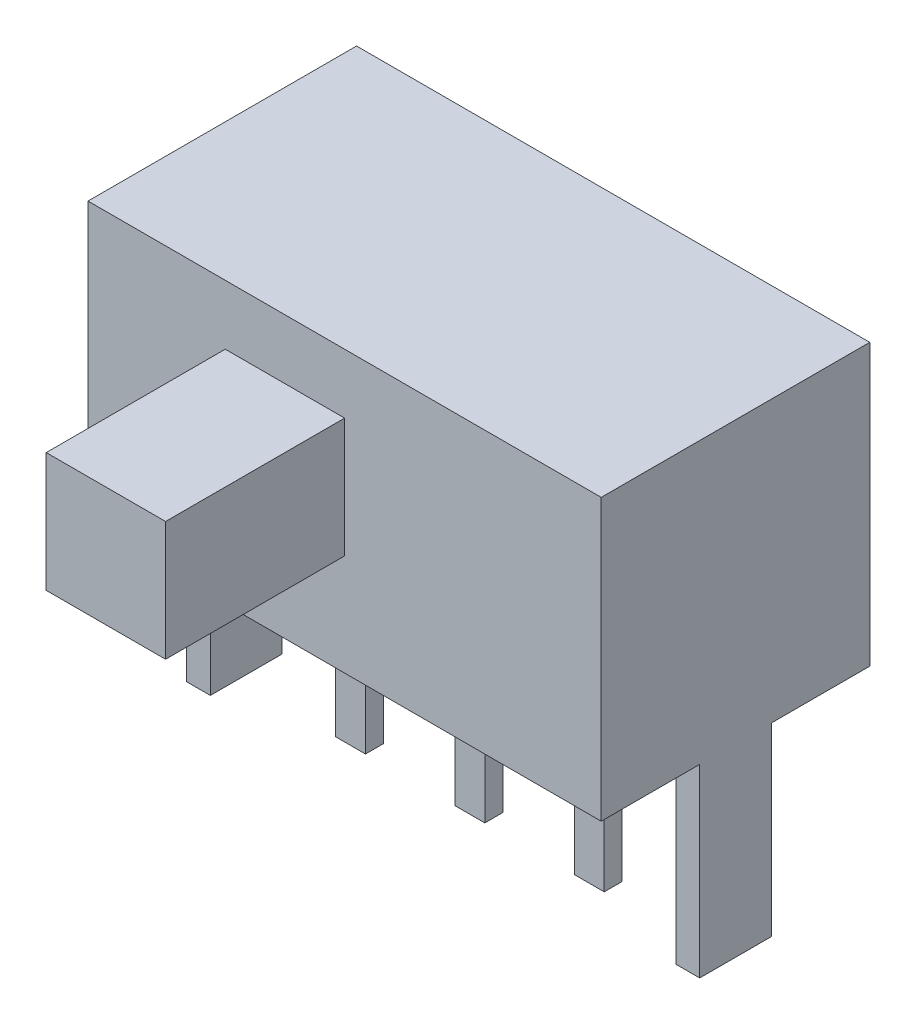
SolidWorks part; units mm, degrees
ref_plane "前视基准面" through (0, 0, 0) normal (0, 0, 1) x (1, 0, 0)
ref_plane "上视基准面" through (0, 0, 0) normal (0, 1, 0) x (1, 0, 0)
ref_plane "右视基准面" through (0, 0, 0) normal (1, 0, 0) x (0, 0, -1)
other "Configuration Table"
sketch "草图1" plane through (0, 0, 0) normal (0, 1, 0) x (1, 0, 0)
  line L1 (0, 0) -> (8.6, 0)
  line L2 (0, 0) -> (0, 4.5)
  line L3 (0, 4.5) -> (8.6, 4.5)
  line L4 (8.6, 0) -> (8.6, 4.5)
  line L5 (0, 0) -> (8.6, 4.5) construction
  line L6 (0, 4.5) -> (8.6, 0) construction
  point P4 (4.3, 2.25)
  dimension "D1" = 4.5
  dimension "D2" = 8.6
extrude "凸台-拉伸1" add sketch "草图1" along normal blind 4.7
sketch "草图2" plane through (0, 0, 0) normal (0, 0, 1) x (1, 0, 0)
  line L0 (0, 0) -> (8.6, 0) construction
  line L1 (2.3, 3.7) -> (4.3, 3.7)
  line L2 (2.3, 3.7) -> (2.3, 1.7)
  line L3 (2.3, 1.7) -> (4.3, 1.7)
  line L4 (4.3, 3.7) -> (4.3, 1.7)
  line L5 (2.3, 3.7) -> (4.3, 1.7) construction
  line L6 (2.3, 1.7) -> (4.3, 3.7) construction
  line L7 (4.3, 0) -> (4.3, 4.7) construction
  line L8 (0, 4.7) -> (8.6, 4.7) construction
  point P4 (3.3, 2.7)
  dimension "D1" = 2.7
  dimension "D2" = 2
  dimension "D3" = 2
extrude "凸台-拉伸2" add sketch "草图2" along normal blind 3
sketch "草图4" plane through (0, 0, 0) normal (0, -1, 0) x (1, 0, 0)
  line L0 (0, -4.5) -> (0, 0) construction
  line L1 (0, -1.65) -> (0.4, -1.65)
  line L2 (0, -1.65) -> (0, -2.85)
  line L3 (0, -2.85) -> (0.4, -2.85)
  line L4 (0.4, -1.65) -> (0.4, -2.85)
  line L5 (0, -1.65) -> (0.4, -2.85) construction
  line L6 (0, -2.85) -> (0.4, -1.65) construction
  line L7 (8.6, 0) -> (8.6, -4.5) construction
  line L8 (8.6, -1.65) -> (8.2, -1.65)
  line L9 (8.6, -1.65) -> (8.6, -2.85)
  line L10 (8.6, -2.85) -> (8.2, -2.85)
  line L11 (8.2, -1.65) -> (8.2, -2.85)
  line L12 (8.6, -1.65) -> (8.2, -2.85) construction
  line L13 (8.6, -2.85) -> (8.2, -1.65) construction
  line L14 (0, -2.25) -> (8.6, -2.25) construction
  point P4 (0.2, -2.25)
  point P11 (8.4, -2.25)
  point P16 (8.4014, -2.25)
  point P17 (0.2133, -2.25)
  point P18 (8.4, -2.25)
  point P19 (0.2, -2.25)
  dimension "D1" = 1.2
  dimension "D2" = 1.2
  dimension "D3" = 0.4
  dimension "D4" = 0.4
extrude "凸台-拉伸3" add sketch "草图4" along normal blind 3.1
sketch "草图5" plane through (0, 0, 0) normal (0, -1, 0) x (1, 0, 0)
  line L0 (0.4, -2.25) -> (8.2, -2.25) construction
  line L1 (4.05, -2.1) -> (4.55, -2.1)
  line L2 (4.05, -2.1) -> (4.05, -2.4)
  line L3 (4.05, -2.4) -> (4.55, -2.4)
  line L4 (4.55, -2.1) -> (4.55, -2.4)
  line L5 (4.05, -2.1) -> (4.55, -2.4) construction
  line L6 (4.05, -2.4) -> (4.55, -2.1) construction
  line L7 (0.4, -2.85) -> (0.4, -1.65) construction
  line L8 (8.2, -1.65) -> (8.2, -2.85) construction
  line L9 (6.05, -2.1) -> (6.05, -2.4)
  line L10 (6.05, -2.1) -> (6.55, -2.1)
  line L11 (6.55, -2.1) -> (6.55, -2.4)
  line L12 (6.05, -2.4) -> (6.55, -2.4)
  line L13 (4.05, -2.1) -> (6.05, -2.1) construction
  line L14 (4.3, -2.25) -> (4.3, -4.5) construction
  line L15 (8.6, -4.5) -> (0, -4.5) construction
  line L16 (2.55, -2.1) -> (2.05, -2.1)
  line L17 (2.05, -2.1) -> (2.05, -2.4)
  line L18 (2.55, -2.4) -> (2.05, -2.4)
  line L19 (2.55, -2.1) -> (2.55, -2.4)
  point P4 (4.3, -2.25)
  dimension "D1" = 0.5
  dimension "D2" = 0.3
  dimension "D4" = 2
  dimension "D3" = 2
extrude "凸台-拉伸4" add sketch "草图5" along normal blind 3.1
